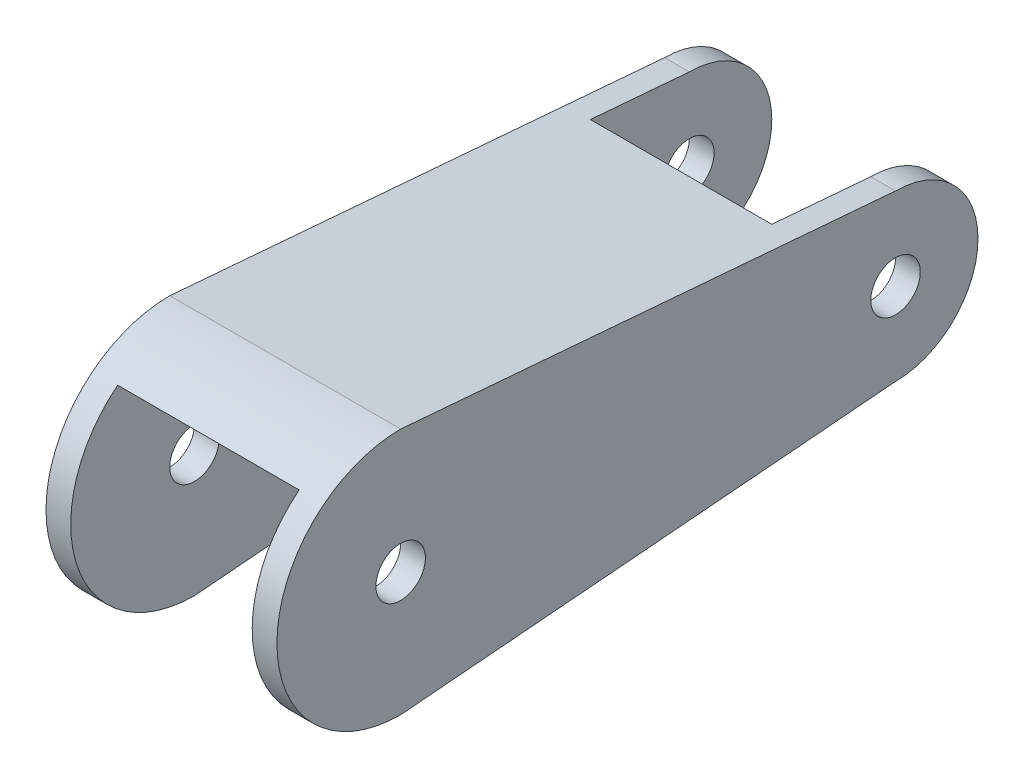
SolidWorks part; units mm, degrees
ref_plane "Front Plane" through (0, 0, 0) normal (0, 0, 1) x (1, 0, 0)
ref_plane "Top Plane" through (0, 0, 0) normal (0, 1, 0) x (1, 0, 0)
ref_plane "Right Plane" through (0, 0, 0) normal (1, 0, 0) x (0, 0, -1)
sketch "Sketch1" plane through (0, 0, 0) normal (1, 0, 0) x (0, 0, -1)
  line L0 (0, 0) -> (150, 0) construction
  line L1 (0, 37.5) -> (150, 25)
  line L2 (0, -37.5) -> (150, -25)
  arc A0 (0, 37.5) -> (0, -37.5) centre (0, 0) ccw
  arc A1 (150, -25) -> (150, 25) centre (150, 0) ccw
  dimension "D1" = 75
  dimension "D2" = 50
  dimension "D3" = 150
extrude "Boss-Extrude1" add sketch "Sketch1" along normal blind 70
sketch "Sketch2" plane through (0, 0, 0) normal (0, 1, 0) x (1, 0, 0)
  line L0 (70, 175) -> (0, 175) construction
  line L1 (7.5, 175) -> (62.5, 175)
  line L2 (7.5, 175) -> (7.5, 120)
  line L3 (7.5, 120) -> (62.5, 120)
  line L4 (62.5, 175) -> (62.5, 120)
  line L6 (35, 175) -> (35, 120) construction
  line L7 (70, 0) -> (0, 0) construction
  point P9 (35, 0)
  dimension "D1" = 55
  dimension "D2" = 55
extrude "Cut-Extrude1" cut sketch "Sketch2" along normal through all both and the other way through all
sketch "Sketch4" plane through (0, 37.2414, -3.1034) normal (0, 0.9965, -0.083) x (1, 0, 0)
  line L1 (62.5, 121.8692) -> (7.5, 121.8692)
  line L2 (62.5, 121.8692) -> (62.5, -37.5)
  line L3 (62.5, -37.5) -> (7.5, -37.5)
  line L4 (7.5, 121.8692) -> (7.5, -37.5)
  line L5 (7.5, 147.4057) -> (7.5, 117.3017) construction
  line L6 (0, -37.5) -> (70, -37.5) construction
  line L7 (62.5, 121.8692) -> (7.5, 121.8692) construction
  line L8 (62.5, 117.3017) -> (62.5, 147.4057) construction
extrude "Cut-Extrude2" cut sketch "Sketch4" against normal up to surface (44.81 mm away) from offset 10 offset against normal yes
sketch "Sketch7" plane through (70, 0, 0) normal (1, 0, 0) x (0, 0, -1)
  circle A0 centre (0, 0) radius 7.5
  dimension "D1" = 15
extrude "Cut-Extrude4" cut sketch "Sketch7" against normal through all
sketch "Sketch8" plane through (70, 0, 0) normal (1, 0, 0) x (0, 0, -1)
  circle A0 centre (150, 0) radius 7.5
  arc A1 (150, -25) -> (150, 25) centre (150, 0) ccw construction
  dimension "D1" = 15
extrude "Cut-Extrude5" cut sketch "Sketch8" against normal through all
sketch3d "3DSketch1" plane through (0, 0, 0) normal (0, 0, 1) x (1, 0, 0)
  dimension "D1" = 30
